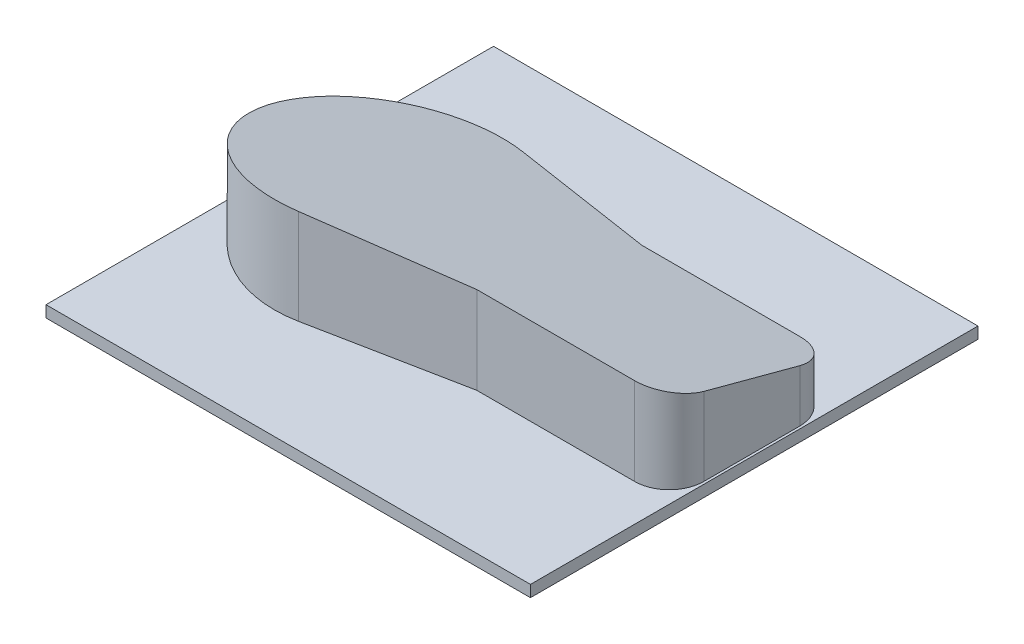
SolidWorks part; units mm, degrees
ref_plane "前视基准面" through (0, 0, 0) normal (0, 0, 1) x (1, 0, 0)
ref_plane "上视基准面" through (0, 0, 0) normal (0, 1, 0) x (1, 0, 0)
ref_plane "右视基准面" through (0, 0, 0) normal (1, 0, 0) x (0, 0, -1)
sketch "草图1" plane through (0, 0, 0) normal (0, 1, 0) x (1, 0, 0)
  line L1 (0, 0) -> (210, 0)
  line L2 (0, 0) -> (0, -194)
  line L3 (0, -194) -> (210, -194)
  line L4 (210, 0) -> (210, -194)
  dimension "D1" = 194
  dimension "D2" = 210
extrude "凸台-拉伸1" add sketch "草图1" along normal blind 5
sketch "草图2" plane through (0, 5, 0) normal (0, 1, 0) x (1, 0, 0)
  line L0 (210, 0) -> (0, 0) construction
  line L1 (125.5136, -61.2155) -> (208.95, -61.2155)
  line L2 (0, 0) -> (0, -194) construction
  line L3 (208.95, -61.2155) -> (208.95, -132.7845)
  line L4 (208.95, -132.7845) -> (125.5136, -132.7845)
  line L5 (60.058, -53.3915) -> (189.0326, -78.8502) construction
  line L6 (60.058, -140.6085) -> (189.0326, -115.1498) construction
  line L7 (61.0263, -48.4861) -> (190.0009, -73.9449) construction
  line L8 (61.0263, -145.5139) -> (190.0009, -120.0551) construction
  line L9 (61.0263, -48.4861) -> (125.5136, -61.2155)
  line L10 (61.0263, -145.5139) -> (125.5136, -132.7845)
  arc A0 (60.058, -53.3915) -> (60.058, -140.6085) centre (51.45, -97) ccw construction
  arc A1 (189.0326, -115.1498) -> (189.0326, -78.8502) centre (185.45, -97) ccw construction
  arc A2 (190.0009, -120.0551) -> (190.0009, -73.9449) centre (185.45, -97) ccw construction
  arc A3 (61.0263, -48.4861) -> (61.0263, -145.5139) centre (51.45, -97) ccw
  dimension "D1" = 88.9
  dimension "D4" = 37
  dimension "D2" = 97
  dimension "D3" = 51.45
  dimension "D5" = 134
  dimension "D6" = 97
  dimension "D7" = 5
extrude "凸台-拉伸2" add sketch "草图2" along normal blind 50
sketch "草图3" plane through (0, 0, 0) normal (-1, 0, 0) x (0, 0, 1)
  line L5 (146.45, 46.5002) -> (146.45, 55)
  line L6 (146.45, 46.5002) -> (47.55, 20)
  line L7 (47.55, 55) -> (47.55, 5) construction
  line L8 (0, 5) -> (194, 5) construction
  line L10 (146.45, 55) -> (47.55, 55)
  line L11 (47.55, 55) -> (47.55, 20)
  dimension "D1" = 15
  dimension "D2" = 15
extrude "切除-拉伸1" cut sketch "草图3" against normal through all
sketch "草图4" plane through (0, 6.7728, -1.8148) normal (0, 0.9659, -0.2588) x (1, 0, 0)
  line L0 (175.45, -83.8006) -> (185.45, -83.8006)
  line L1 (175.45, -120.8006) -> (185.45, -120.8006)
  line L2 (61.0263, -152.5258) -> (125.5136, -139.3474)
  line L3 (61.0263, -152.5258) -> (125.5136, -139.3474)
  line L11 (125.5136, -139.3474) -> (208.95, -139.3474)
  line L12 (125.5136, -139.3474) -> (208.95, -139.3474)
  line L13 (208.95, -139.3474) -> (208.95, -65.2537)
  line L14 (208.95, -139.3474) -> (208.95, -65.2537)
  line L15 (208.95, -65.2537) -> (125.5136, -65.2537)
  line L16 (208.95, -65.2537) -> (125.5136, -65.2537)
  line L17 (125.5136, -65.2537) -> (61.0263, -52.0753)
  line L18 (125.5136, -65.2537) -> (61.0263, -52.0753)
  circle A0 centre (51.45, -102.3006) radius 44.45
  arc A1 (185.45, -120.8006) -> (185.45, -83.8006) centre (185.45, -102.3006) ccw
  arc A2 (175.45, -83.8006) -> (175.45, -120.8006) centre (175.45, -102.3006) ccw
  ellipse E2 centre (51.45, -102.3006) end of major axis (51.45, -51.1062) minor radius 49.45 (61.0263, -52.0753) -> (61.0263, -152.5258) ccw
  ellipse E4 centre (51.45, -102.3006) end of major axis (51.45, -51.1062) minor radius 49.45 (61.0263, -52.0753) -> (61.0263, -152.5258) ccw
  dimension "D2" = 88.9
  dimension "D3" = 37
  dimension "D4" = 10
  dimension "D1" = 0
fillet "圆角1" radius 15 2 edges at (208.95, 23.9193, 132.7845) (208.95, 14.3308, 61.2155)
sketch "草图5" plane through (0, 0, 0) normal (0, -1, 0) x (1, 0, 0)
  line L0 (124.5361, 122.7845) -> (59.0898, 135.7032)
  line L1 (59.0898, 58.2968) -> (124.5361, 71.2155)
  line L2 (124.5361, 71.2155) -> (193.95, 71.2155)
  line L3 (198.95, 76.2155) -> (198.95, 117.7845)
  line L4 (193.95, 122.7845) -> (124.5361, 122.7845)
  line L5 (193.95, 132.7845) -> (125.5136, 132.7845)
  line L6 (208.95, 76.2155) -> (208.95, 117.7845)
  line L7 (125.5136, 61.2155) -> (193.95, 61.2155)
  line L8 (61.0263, 48.4861) -> (125.5136, 61.2155)
  line L9 (125.5136, 132.7845) -> (61.0263, 145.5139)
  line L10 (193.95, 132.7845) -> (125.5136, 132.7845) construction
  line L11 (208.95, 76.2155) -> (208.95, 117.7845) construction
  line L12 (125.5136, 61.2155) -> (193.95, 61.2155) construction
  line L13 (61.0263, 48.4861) -> (125.5136, 61.2155) construction
  line L14 (125.5136, 132.7845) -> (61.0263, 145.5139) construction
  arc A0 (59.0898, 135.7032) -> (59.0898, 58.2968) centre (51.45, 97) ccw
  arc A1 (193.95, 71.2155) -> (198.95, 76.2155) centre (193.95, 76.2155) ccw
  arc A2 (198.95, 117.7845) -> (193.95, 122.7845) centre (193.95, 117.7845) ccw
  arc A3 (208.95, 117.7845) -> (193.95, 132.7845) centre (193.95, 117.7845) ccw
  arc A4 (193.95, 61.2155) -> (208.95, 76.2155) centre (193.95, 76.2155) ccw
  arc A5 (61.0263, 145.5139) -> (61.0263, 48.4861) centre (51.45, 97) ccw
  arc A6 (208.95, 117.7845) -> (193.95, 132.7845) centre (193.95, 117.7845) ccw construction
  arc A7 (193.95, 61.2155) -> (208.95, 76.2155) centre (193.95, 76.2155) ccw construction
  arc A8 (61.0263, 145.5139) -> (61.0263, 48.4861) centre (51.45, 97) ccw construction
  dimension "D1" = 0
  dimension "D2" = 10
extrude "切除-拉伸2" cut sketch "草图5" against normal blind 15
ref_plane "基准面1" through (0, 1.9431, -0.5207) normal (0, 0.9659, -0.2588) x (1, 0, 0)
sketch "草图7" plane through (0, 1.9431, -0.5207) normal (0, 0.9659, -0.2588) x (1, 0, 0)
  line L0 (124.5023, -129.3474) -> (193.95, -129.3474)
  line L1 (198.95, -123.8183) -> (198.95, -80.7829)
  line L2 (193.95, -75.2537) -> (124.5023, -75.2537)
  line L3 (124.5023, -75.2537) -> (59.0241, -61.8728)
  line L4 (59.0241, -142.7283) -> (124.5023, -129.3474)
  line L5 (125.5136, -139.3474) -> (193.95, -139.3474)
  line L6 (208.95, -123.8183) -> (208.95, -80.7829)
  line L7 (193.95, -65.2537) -> (125.5136, -65.2537)
  line L8 (125.5136, -65.2537) -> (61.0263, -52.0753)
  line L9 (61.0263, -152.5258) -> (125.5136, -139.3474)
  line L10 (125.5136, -139.3474) -> (193.95, -139.3474) construction
  line L11 (208.95, -123.8183) -> (208.95, -80.7829) construction
  line L12 (193.95, -65.2537) -> (125.5136, -65.2537) construction
  line L13 (125.5136, -65.2537) -> (61.0263, -52.0753) construction
  line L14 (61.0263, -152.5258) -> (125.5136, -139.3474) construction
  ellipse E3 centre (193.95, -123.8183) end of major axis (193.95, -108.2891) minor radius 15 (193.95, -139.3474) -> (208.95, -123.8183) ccw
  ellipse E4 centre (193.95, -80.7829) end of major axis (193.95, -65.2537) minor radius 15 (208.95, -80.7829) -> (193.95, -65.2537) ccw
  ellipse E5 centre (51.45, -102.3006) end of major axis (51.45, -51.1062) minor radius 49.45 (61.0263, -52.0753) -> (61.0263, -152.5258) ccw
  ellipse E6 centre (193.95, -123.8183) end of major axis (193.95, -108.2891) minor radius 15 (193.95, -139.3474) -> (208.95, -123.8183) ccw construction
  ellipse E7 centre (193.95, -80.7829) end of major axis (193.95, -65.2537) minor radius 15 (208.95, -80.7829) -> (193.95, -65.2537) ccw construction
  ellipse E8 centre (51.45, -102.3006) end of major axis (51.45, -51.1062) minor radius 49.45 (61.0263, -52.0753) -> (61.0263, -152.5258) ccw construction
  spline S0 degree 1 poles (193.95, -129.3474) (198.95, -123.8183) knots 0 0 1 1 construction
  spline S1 degree 1 poles (198.95, -80.7829) (193.95, -75.2537) knots 0 0 1 1 construction
  spline S2 degree 1 poles (59.0241, -61.8728) (59.0241, -142.7283) knots 0 0 1 1 construction
  spline S3 degree 3 poles (193.95, -129.3474) (194.5624, -129.3474) (195.7746, -129.1021) (197.4397, -127.9699) (198.6508, -126.1275) (198.95, -124.5744) (198.95, -123.8183) knots -3.141593 -3.141593 -3.141593 -3.141593 -2.748894 -2.356194 -1.963495 -1.570796 -1.570796 -1.570796 -1.570796
  spline S4 degree 3 poles (198.95, -80.7829) (198.95, -80.0267) (198.6508, -78.4736) (197.4397, -76.6312) (195.7746, -75.4991) (194.5624, -75.2537) (193.95, -75.2537) knots -1.570796 -1.570796 -1.570796 -1.570796 -1.178097 -0.785398 -0.392699 0 0 0 0
  spline S5 degree 3 poles (59.0241, -61.8728) (56.2101, -61.2977) (50.428, -60.7897) (38.9641, -62.4133) (25.7313, -69.2976) (14.6549, -83.9722) (10.6725, -102.3006) (14.6549, -120.6289) (25.7313, -135.3035) (38.9641, -142.1879) (50.428, -143.8114) (56.2101, -143.3034) (59.0241, -142.7283) knots -0.194888 -0.194888 -0.194888 -0.194888 0.025822 0.246533 0.687954 1.129375 1.570796 2.012217 2.453639 2.89506 3.11577 3.336481 3.336481 3.336481 3.336481
  dimension "D1" = 0
  dimension "D2" = 10
extrude "切除-拉伸4" cut sketch "草图7" against normal blind 5
sketch "草图8" plane through (0, 15, 0) normal (0, -1, 0) x (1, 0, 0)
  line L5 (193.95, 122.7845) -> (124.5361, 122.7845)
  line L6 (124.5361, 122.7845) -> (59.0898, 135.7032)
  line L7 (59.0898, 58.2968) -> (124.5361, 71.2155)
  line L8 (124.5361, 71.2155) -> (193.95, 71.2155)
  line L9 (198.95, 76.2155) -> (198.95, 117.7845)
  line L10 (193.95, 122.7845) -> (124.5361, 122.7845)
  line L11 (124.5361, 122.7845) -> (59.0898, 135.7032)
  line L12 (59.0898, 58.2968) -> (124.5361, 71.2155)
  line L13 (124.5361, 71.2155) -> (193.95, 71.2155)
  line L14 (198.95, 76.2155) -> (198.95, 117.7845)
  arc A3 (59.0898, 135.7032) -> (59.0898, 58.2968) centre (51.45, 97) ccw
  arc A4 (193.95, 71.2155) -> (198.95, 76.2155) centre (193.95, 76.2155) ccw
  arc A5 (198.95, 117.7845) -> (193.95, 122.7845) centre (193.95, 117.7845) ccw
  arc A6 (59.0898, 135.7032) -> (59.0898, 58.2968) centre (51.45, 97) ccw
  arc A7 (193.95, 71.2155) -> (198.95, 76.2155) centre (193.95, 76.2155) ccw
  arc A8 (198.95, 117.7845) -> (193.95, 122.7845) centre (193.95, 117.7845) ccw
  dimension "D1" = 0
extrude "切除-拉伸6" cut sketch "草图8" against normal up to surface (7.5045 mm away)
